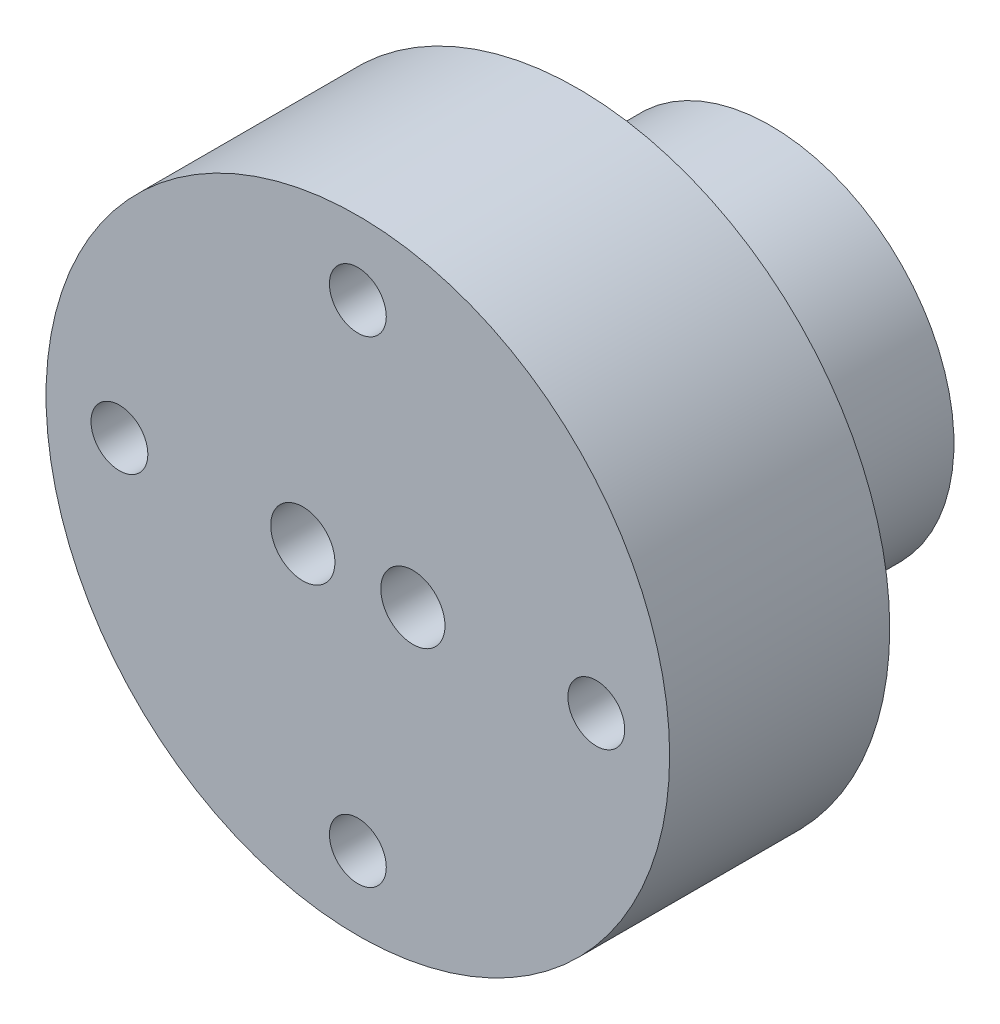
SolidWorks part; units mm, degrees
ref_plane "Front Plane" through (0, 0, 0) normal (0, 0, 1) x (1, 0, 0)
ref_plane "Top Plane" through (0, 0, 0) normal (0, 1, 0) x (1, 0, 0)
ref_plane "Right Plane" through (0, 0, 0) normal (1, 0, 0) x (0, 0, -1)
sketch "Sketch1" plane through (0, 0, 0) normal (0, 0, 1) x (1, 0, 0)
  circle A0 centre (0, 0) radius 10
  dimension "D1" = 20
extrude "Boss-Extrude1" add sketch "Sketch1" along normal blind 10.5
sketch "Sketch3" plane through (0, 0, 10.5) normal (0, 0, 1) x (1, 0, 0)
  circle A0 centre (0, 0) radius 17
  dimension "D1" = 34
extrude "Boss-Extrude2" add sketch "Sketch3" along normal blind 12 contours A0
sketch "Sketch4" plane through (0, 0, 22.5) normal (0, 0, 1) x (1, 0, 0)
  line L0 (0, 0) -> (17.1689, 0) construction
  line L1 (0, -17.3559) -> (0, 16.6078) construction
  circle A0 centre (3, 0) radius 1.55
  circle A1 centre (-3, 0) radius 1.55
  dimension "D1" = 3.1
  dimension "D2" = 3
extrude "Cut-Extrude3" cut sketch "Sketch4" against normal through all
sketch "Sketch5" plane through (0, 0, 22.5) normal (0, 0, 1) x (1, 0, 0)
  line L0 (0, 0) -> (20.7598, 0) construction
  circle A0 centre (0, 0) radius 13 construction
  circle A1 centre (13, 0) radius 1.55
  circle A2 centre (0, -13) radius 1.55
  circle A3 centre (-13, 0) radius 1.55
  circle A4 centre (0, 13) radius 1.55
  point P15 (0, 0)
  dimension "D1" = 26
  dimension "D2" = 3.1
  dimension "D3" = 4
extrude "Cut-Extrude5" cut sketch "Sketch5" against normal through all
sketch "Sketch6" plane through (0, 0, 10.5) normal (0, 0, -1) x (-1, 0, 0)
  circle A0 centre (13, 0) radius 1.75
  circle A1 centre (0, -13) radius 1.75
  circle A2 centre (-13, 0) radius 1.75
  circle A3 centre (0, 13) radius 1.75
  point P12 (0, 0)
  dimension "D1" = 3.5
  dimension "D2" = 4
extrude "Cut-Extrude6" cut sketch "Sketch6" against normal blind 5.2
sketch "Sketch7" plane through (0, 0, 22.5) normal (0, 0, 1) x (1, 0, 0)
  circle A0 centre (3, 0) radius 1.75
  circle A1 centre (-3, 0) radius 1.75
  dimension "D1" = 3.5
  dimension "D2" = 3.5
extrude "Cut-Extrude7" cut sketch "Sketch7" against normal blind 5.2
